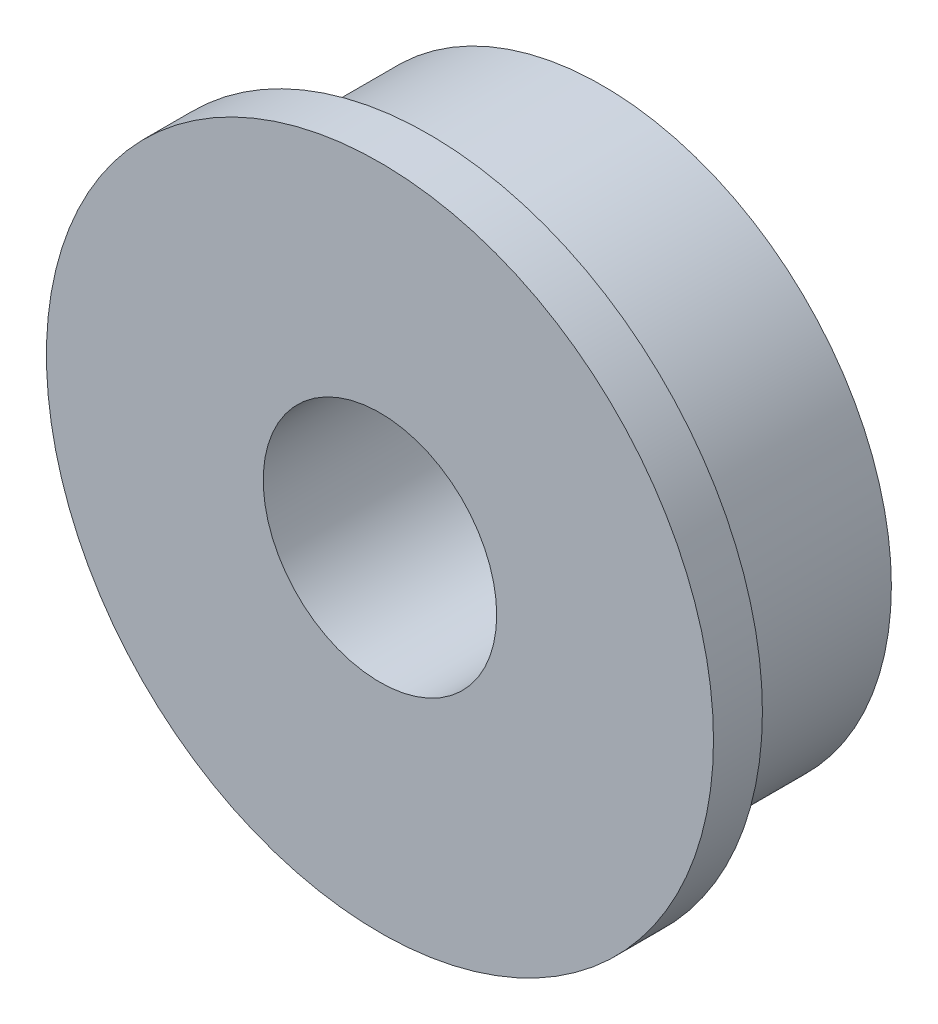
SolidWorks part; units mm, degrees
ref_plane "前视基准面" through (0, 0, 0) normal (0, 0, 1) x (1, 0, 0)
ref_plane "上视基准面" through (0, 0, 0) normal (0, 1, 0) x (1, 0, 0)
ref_plane "右视基准面" through (0, 0, 0) normal (1, 0, 0) x (0, 0, -1)
sketch "草图1" plane through (0, 0, 0) normal (0, 0, 1) x (1, 0, 0)
  circle A0 centre (0, 0) radius 6.5
  circle A1 centre (0, 0) radius 2.625
  dimension "D1" = 13
  dimension "D2" = 5.25
extrude "凸台-拉伸1" add sketch "草图1" along normal blind 3.9
sketch "草图2" plane through (0, 0, 3.9) normal (0, 0, 1) x (1, 0, 0)
  circle A0 centre (0, 0) radius 2.625
  circle A1 centre (0, 0) radius 7.5
  dimension "D1" = 15
  dimension "D2" = 5.25
extrude "凸台-拉伸2" add sketch "草图2" along normal blind 1.1
